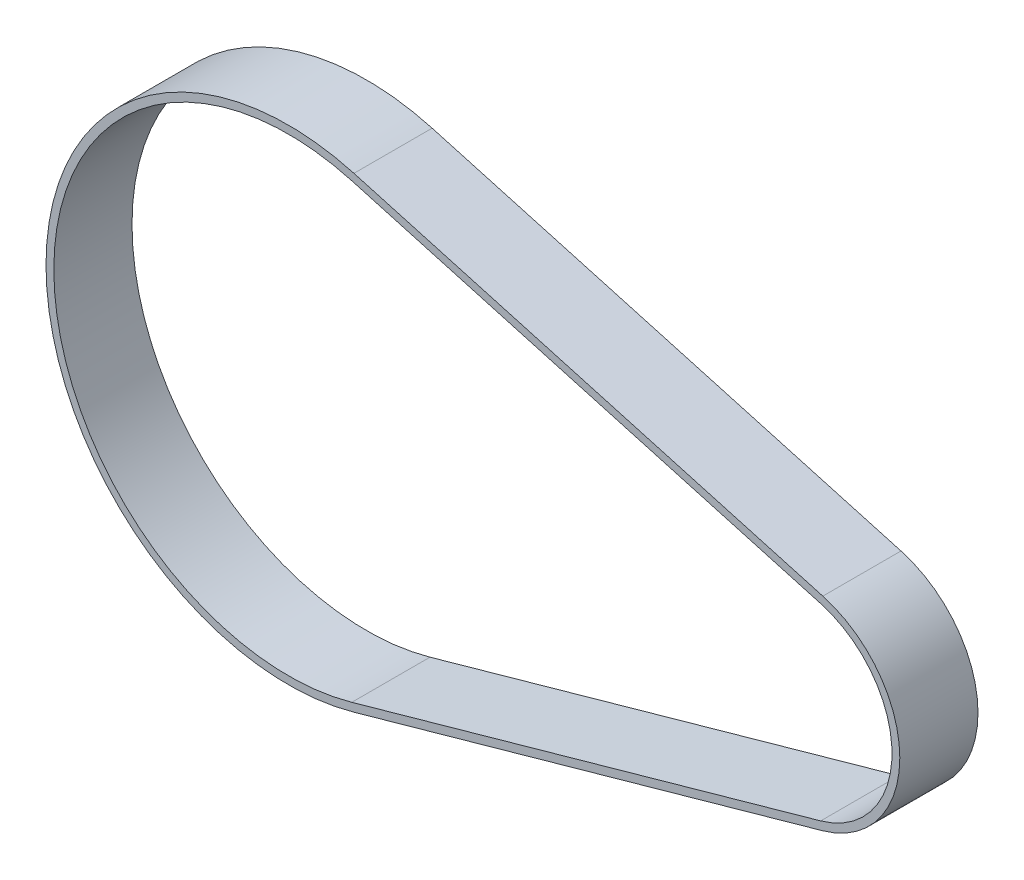
SolidWorks part; units mm, degrees
ref_plane "前视基准面" through (0, 0, 0) normal (0, 0, 1) x (1, 0, 0)
ref_plane "上视基准面" through (0, 0, 0) normal (0, 1, 0) x (1, 0, 0)
ref_plane "右视基准面" through (0, 0, 0) normal (1, 0, 0) x (0, 0, -1)
sketch "草图1" plane through (0, 0, 0) normal (0, 0, 1) x (1, 0, 0)
  line L0 (-1000, 0) -> (49000, 0) construction
  line L1 (3.381, 12.0341) -> (-56.5856, 28.8818)
  line L2 (-56.5856, -28.8818) -> (3.381, -12.0341)
  line L3 (3.6515, 12.9968) -> (-56.3151, 29.8445)
  line L4 (-56.3151, -29.8445) -> (3.6515, -12.9968)
  arc A0 (3.381, -12.0341) -> (3.381, 12.0341) centre (0, 0) ccw
  arc A1 (-56.5856, 28.8818) -> (-56.5856, -28.8818) centre (-64.7, 0) ccw
  arc A2 (-56.3151, 29.8445) -> (-56.3151, -29.8445) centre (-64.7, 0) ccw
  arc A3 (3.6515, -12.9968) -> (3.6515, 12.9968) centre (0, 0) ccw
  dimension "D1" = 60
  dimension "D3" = 25
  dimension "D2" = 64.7
  dimension "D4" = 1
extrude "拉伸1" add sketch "草图1" along normal blind 10
